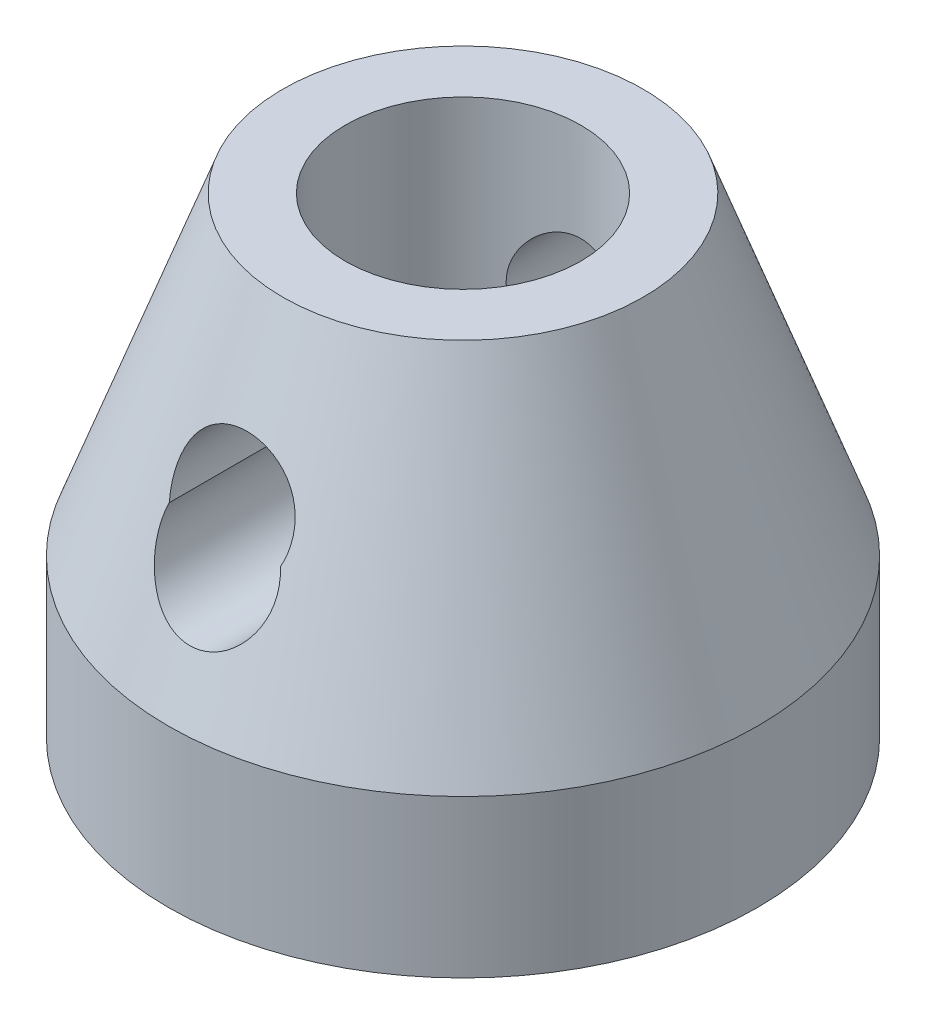
SolidWorks part; units mm, degrees
ref_plane "Front Plane" through (0, 0, 0) normal (0, 0, 1) x (1, 0, 0)
ref_plane "Top Plane" through (0, 0, 0) normal (0, 1, 0) x (1, 0, 0)
ref_plane "Right Plane" through (0, 0, 0) normal (1, 0, 0) x (0, 0, -1)
sketch "Sketch1" plane through (0, 0, 0) normal (0, 1, 0) x (1, 0, 0)
  circle A0 centre (0, 0) radius 7.5
  dimension "D1" = 15
extrude "Boss-Extrude1" add sketch "Sketch1" along normal blind 4
sketch "Sketch4" plane through (0, 4, 0) normal (0, 1, 0) x (1, 0, 0)
  circle A0 centre (0, 0) radius 7.5
extrude "Boss-Extrude4" add sketch "Sketch4" along normal blind 8 draft 20
sketch "Sketch5" plane through (0, 0, 0) normal (0, -1, 0) x (-1, 0, 0)
  circle A0 centre (0, 0) radius 1.5
  dimension "D1" = 3
extrude "Cut-Extrude2" cut sketch "Sketch5" against normal through all
sketch "Sketch6" plane through (0, 12, 0) normal (0, 1, 0) x (1, 0, 0)
  circle A0 centre (0, 0) radius 3
  dimension "D1" = 6
extrude "Cut-Extrude3" cut sketch "Sketch6" against normal blind 9
ref_plane "Plane1" through (0, 0, 10) normal (0, 0, 1) x (1, 0, 0)
sketch "Sketch7" plane through (0, 0, 10) normal (0, 0, 1) x (1, 0, 0)
  line L0 (4.5882, 12) -> (-4.5882, 12) construction
  circle A0 centre (0, 8) radius 1.5
  dimension "D1" = 3
  dimension "D2" = 4
extrude "Cut-Extrude4" cut sketch "Sketch7" against normal through all
sketch "Sketch8" plane through (0, 0, 10) normal (0, 0, 1) x (1, 0, 0)
  circle A0 centre (0, 7) radius 1.5
  circle A1 centre (0, 8) radius 1.5 construction
  dimension "D1" = 3
  dimension "D2" = 1
extrude "Cut-Extrude5" cut sketch "Sketch8" against normal through all
